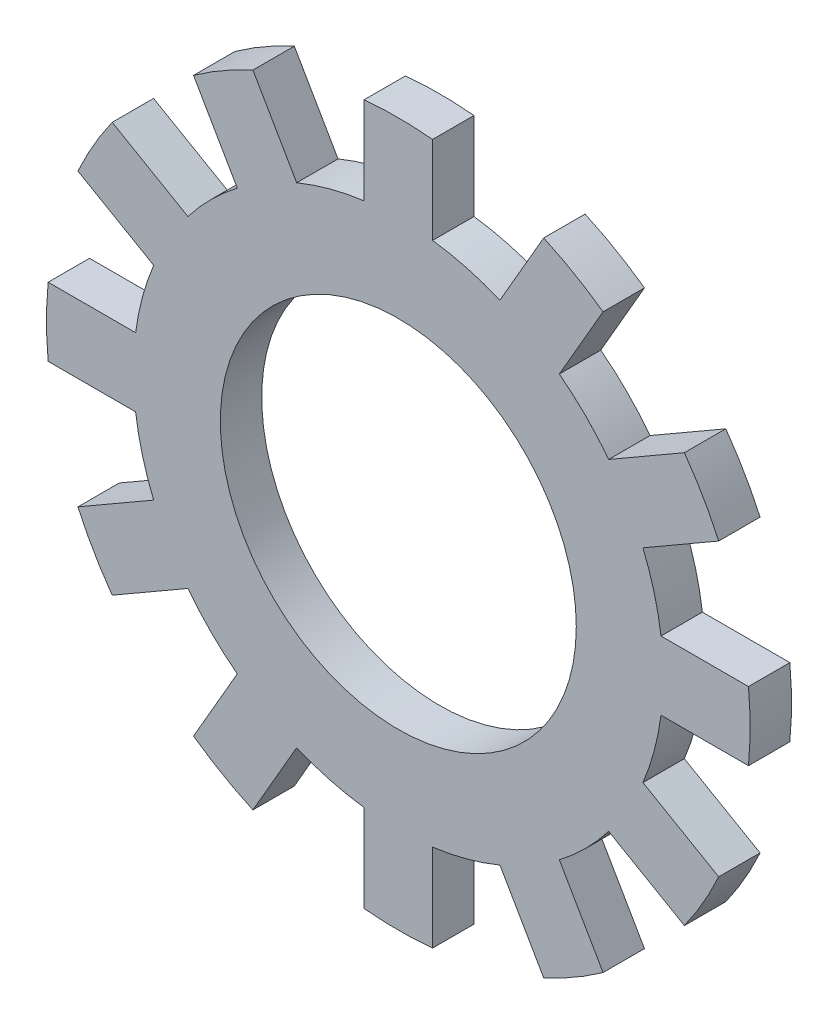
SolidWorks part; units mm, degrees
ref_plane "Front Plane" through (0, 0, 0) normal (0, 0, 1) x (1, 0, 0)
ref_plane "Top Plane" through (0, 0, 0) normal (0, 1, 0) x (1, 0, 0)
ref_plane "Right Plane" through (0, 0, 0) normal (1, 0, 0) x (0, 0, -1)
sketch "Sketch1" plane through (0, 0, 0) normal (0, 0, 1) x (1, 0, 0)
  circle A0 centre (0, 0) radius 4.25 construction
  circle A1 centre (0, 0) radius 2.15
  circle A2 centre (0, 0) radius 3.2
  dimension "A" = 4.3
  dimension "B" = 8.5
  dimension "D1" = 6.4
extrude "Extrude1" add sketch "Sketch1" along normal blind 0.5
sketch "Sketch2" plane through (0, 0, 0) normal (0, 0, 1) x (1, 0, 0)
  line L0 (0, 0) -> (0, 4.25) construction
  line L1 (0, 0) -> (1.1, 4.1052) construction
  line L2 (0, 0) -> (-1.1, 4.1052) construction
  line L3 (-0.8282, 3.091) -> (0, 3.091) construction
  line L4 (-0.4141, 4.2298) -> (-0.4141, 3.1731)
  line L5 (0.4141, 4.2298) -> (0.4141, 3.1731)
  line L6 (-0.4141, 3.1731) -> (0.4141, 3.1731)
  circle A0 centre (0, 0) radius 3.2 construction
  circle A1 centre (0, 0) radius 3.2 construction
  circle A2 centre (0, 0) radius 4.25 construction
  arc A3 (0.4141, 4.2298) -> (-0.4141, 4.2298) centre (0, 0) ccw
  dimension "D2" = 15
  dimension "D3" = 15
extrude "Extrude2" add sketch "Sketch2" along normal up to surface (0.5 mm away) up to face at (3.2, 0, 0.5)
pattern_circular "CirPattern1" count 12 over 360 about axis through (0, 0, 0) along (0, 0, 1) of "Extrude2"
sketch "Sketch3" plane through (0, 0, 0) normal (0, 0, 1) x (1, 0, 0)
  line L0 (-0.4944, 4.2211) -> (-0.4944, 3.1616)
  line L1 (0.4944, 4.2211) -> (0.4944, 3.1616)
  line L2 (0, 0) -> (0, 4.25) construction
  line L3 (0, 0) -> (1.3133, 4.042) construction
  line L4 (0, 0) -> (-1.3133, 4.042) construction
  line L5 (-0.9889, 3.0434) -> (0, 3.0434) construction
  line L6 (-0.4944, 3.1616) -> (0.4944, 3.1616)
  circle A0 centre (0, 0) radius 4.25 construction
  circle A1 centre (0, 0) radius 3.2 construction
  circle A2 centre (0, 0) radius 3.2 construction
  arc A3 (0.4944, 4.2211) -> (-0.4944, 4.2211) centre (0, 0) ccw
  dimension "D2" = 18
  dimension "D3" = 18
extrude "Extrude3" [suppressed] add sketch "Sketch3" along normal up to surface (0.45 mm away)
pattern_circular "CirPattern2" [suppressed] count 10 over 360
equation "\"D1@Sketch1\" =  ( \"B@Sketch1\" + \"A@Sketch1\" )  / 2"
